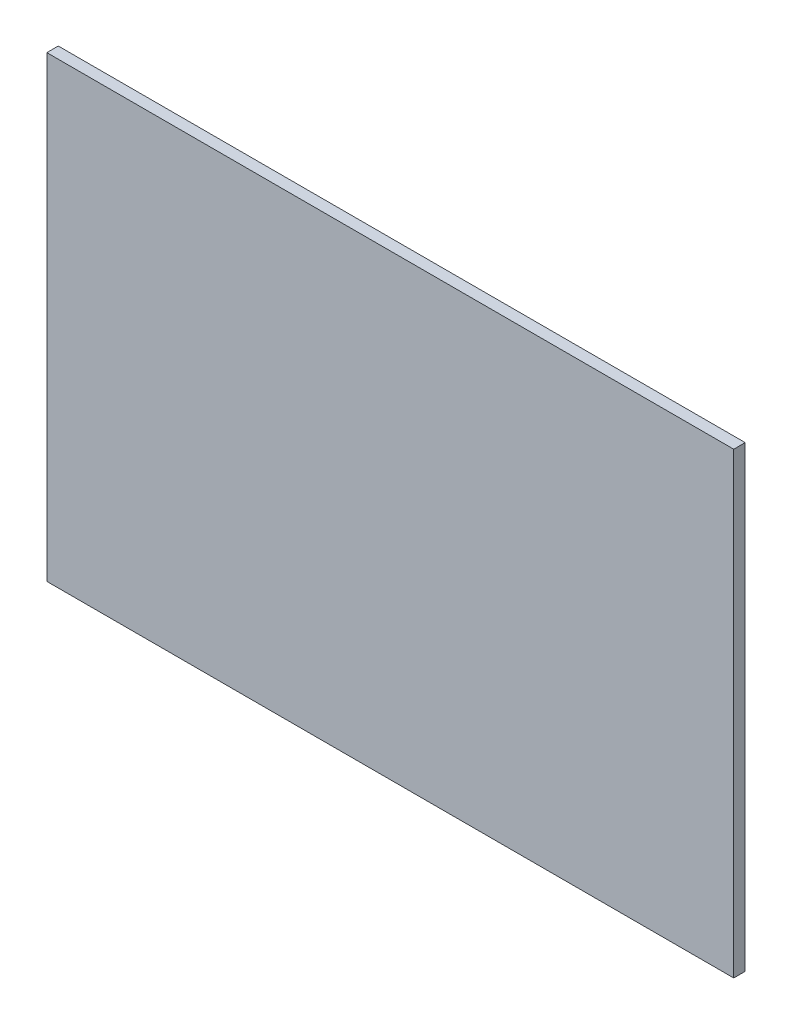
SolidWorks part; units mm, degrees
ref_plane "Front Plane" through (0, 0, 0) normal (0, 0, 1) x (1, 0, 0)
ref_plane "Top Plane" through (0, 0, 0) normal (0, 1, 0) x (1, 0, 0)
ref_plane "Right Plane" through (0, 0, 0) normal (1, 0, 0) x (0, 0, -1)
sketch "Sketch1" plane through (0, 0, 0) normal (0, 0, 1) x (1, 0, 0)
  line L1 (300, -200) -> (-300, -200)
  line L2 (300, -200) -> (300, 200)
  line L3 (300, 200) -> (-300, 200)
  line L4 (-300, -200) -> (-300, 200)
  line L5 (300, -200) -> (-300, 200) construction
  line L6 (300, 200) -> (-300, -200) construction
  point P0 (0, 0)
extrude "Boss-Extrude1" add sketch "Sketch1" along normal blind 10
